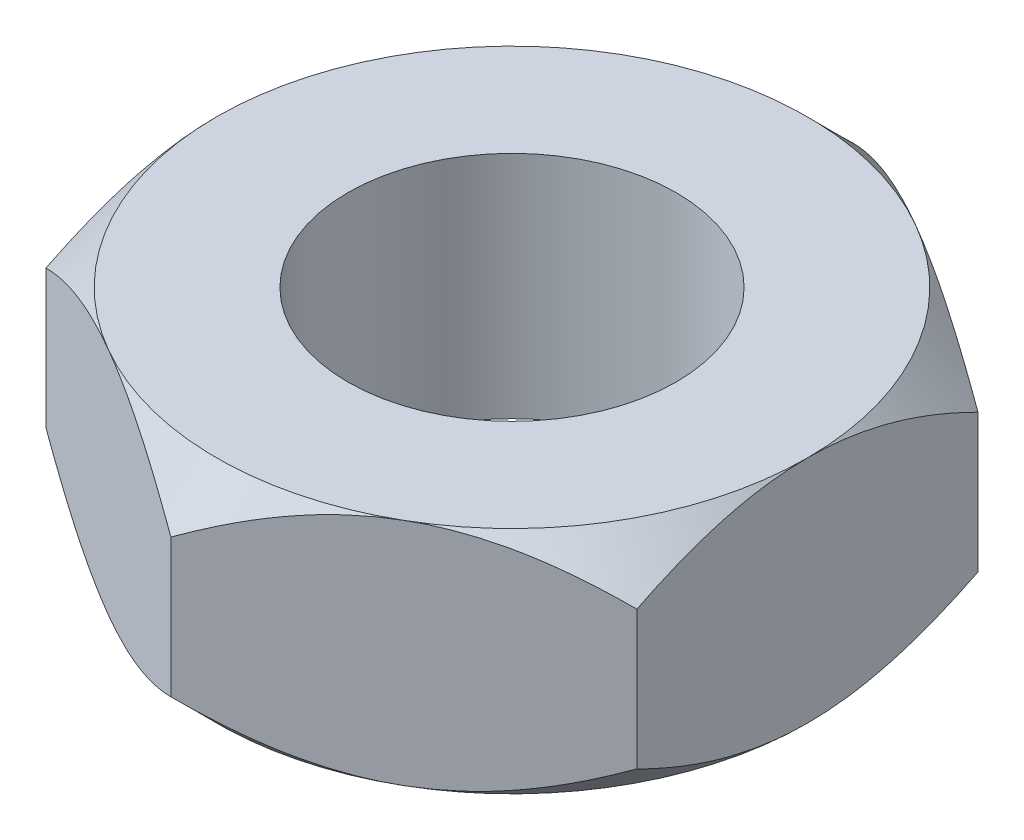
SolidWorks part; units mm, degrees
material "Plain Carbon Steel"
ref_plane "Front Plane" through (0, 0, 0) normal (0, 0, 1) x (1, 0, 0)
ref_plane "Top Plane" through (0, 0, 0) normal (0, 1, 0) x (1, 0, 0)
ref_plane "Right Plane" through (0, 0, 0) normal (1, 0, 0) x (0, 0, -1)
sketch "Sketch1" plane through (0, 0, 0) normal (0, 1, 0) x (1, 0, 0)
  line L1 (0, 5.1962) -> (-4.5, 2.5981)
  line L2 (-4.5, 2.5981) -> (-4.5, -2.5981)
  line L3 (-4.5, -2.5981) -> (0, -5.1962)
  line L4 (0, -5.1962) -> (4.5, -2.5981)
  line L5 (4.5, -2.5981) -> (4.5, 2.5981)
  line L6 (4.5, 2.5981) -> (0, 5.1962)
  circle A0 centre (0, 0) radius 2.5
  circle A1 centre (0, 0) radius 4.5 construction
  dimension "D1" = 5
  dimension "D2" = 9
extrude "Boss-Extrude1" add sketch "Sketch1" along normal mid plane 3.5
sketch "Sketch2" plane through (0, 1.75, 0) normal (0, 1, 0) x (1, 0, 0)
  line L0 (-4.5, 2.5981) -> (-4.5, -2.5981) construction
  circle A0 centre (0, 0) radius 4.5
sketch "Sketch3" plane through (0, 0, 0) normal (0, 0, 1) x (1, 0, 0)
  line L0 (-5.25, 1) -> (-4.5, 1.75)
  line L3 (-4.5, 1.75) -> (-5.25, 1.75)
  line L4 (-5.25, 1.75) -> (-5.25, 1)
  dimension "D1" = 0.75
  dimension "D2" = 0.75
sweep "Cut-Sweep1" cut profiles "Sketch3" path "Sketch2"
mirror "Mirror1" about plane through (0, 0, 0) normal (0, 1, 0) of "Cut-Sweep1"
